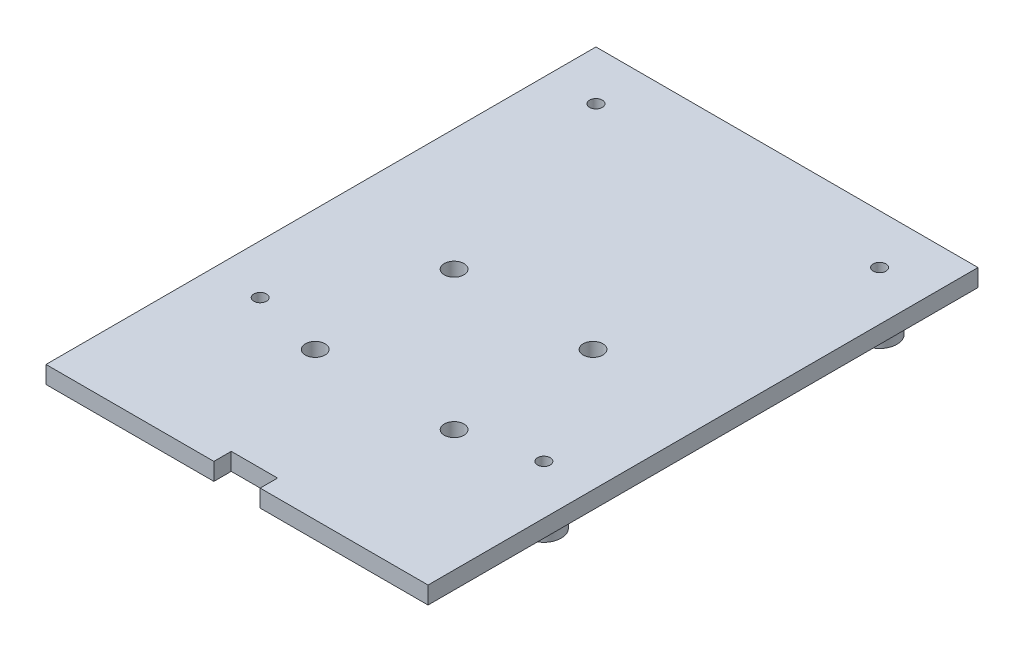
SolidWorks part; units mm, degrees
ref_plane "Front Plane" through (0, 0, 0) normal (0, 0, 1) x (1, 0, 0)
ref_plane "Top Plane" through (0, 0, 0) normal (0, 1, 0) x (1, 0, 0)
ref_plane "Right Plane" through (0, 0, 0) normal (1, 0, 0) x (0, 0, -1)
sketch "Sketch1" plane through (0, 0, 0) normal (0, 1, 0) x (1, 0, 0)
  line L1 (-131, 57.5) -> (-65, 57.5)
  line L2 (-131, 57.5) -> (-131, -37.5)
  line L3 (-131, -37.5) -> (-65, -37.5)
  line L4 (-65, 57.5) -> (-65, -37.5)
extrude "Cradle Base" add sketch "Sketch1" against normal blind 3
sketch "Sketch2" plane through (0, 0, 0) normal (0, 1, 0) x (1, 0, 0)
  circle A0 centre (-122.5, 49) radius 3
  circle A1 centre (-122.5, -9) radius 3
  circle A2 centre (-73.5, 49) radius 3
  circle A3 centre (-73.5, -9) radius 3
extrude "Standoffs" add sketch "Sketch2" against normal blind 10
sketch "Sketch3" plane through (0, 0, 0) normal (0, 1, 0) x (1, 0, 0)
  circle A0 centre (-122.5, 49) radius 1.1
  circle A1 centre (-122.5, -9) radius 1.1
  circle A2 centre (-73.5, 49) radius 1.1
  circle A3 centre (-73.5, -9) radius 1.1
  circle A4 centre (-110, -12) radius 1.7
  circle A5 centre (-110, 12) radius 1.7
  circle A6 centre (-86, -12) radius 1.7
  circle A7 centre (-86, 12) radius 1.7
extrude "Pilot and Bolt Holes" cut sketch "Sketch3" against normal through all and the other way through all
sketch "Sketch4" plane through (0, 0, 0) normal (0, 1, 0) x (1, 0, 0)
  line L1 (-102, -34.5) -> (-94, -34.5)
  line L2 (-102, -34.5) -> (-102, -38.5)
  line L3 (-102, -38.5) -> (-94, -38.5)
  line L4 (-94, -34.5) -> (-94, -38.5)
extrude "USB End Notch" cut sketch "Sketch4" against normal through all and the other way through all
equation "\"BaseT\" = 3.0"
equation "\"StandH\" = 7.0"
equation "\"StandD\" = 6.0"
equation "\"PilotD\" = 2.2"
equation "\"BoltD\" = 3.4"
equation "\"PiCX\" = -98.0"
equation "\"PiCZ\" = -20.0"
equation "\"HoleL\" = 58.0"
equation "\"HoleW\" = 49.0"
